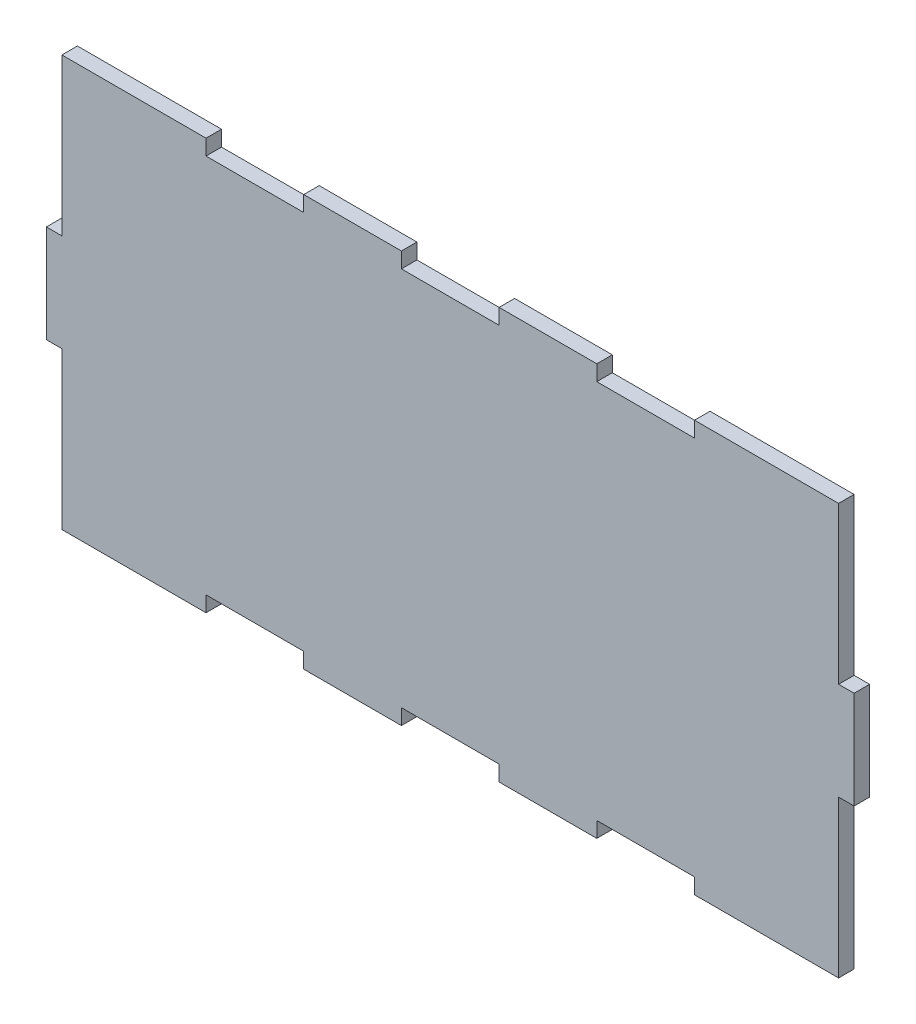
SolidWorks part; units mm, degrees
ref_plane "Plan de face" through (0, 0, 0) normal (0, 0, 1) x (1, 0, 0)
ref_plane "Plan de dessus" through (0, 0, 0) normal (0, 1, 0) x (1, 0, 0)
ref_plane "Plan de droite" through (0, 0, 0) normal (1, 0, 0) x (0, 0, -1)
sketch "Esquisse1" plane through (0, 0, 0) normal (0, 0, 1) x (1, 0, 0)
  line L0 (-82.675, 42.073) -> (-82.675, -42.073)
  line L1 (-82.675, 42.073) -> (82.675, 42.073)
  line L3 (-82.675, -42.073) -> (82.675, -42.073)
  line L4 (82.675, 42.073) -> (82.675, -42.073)
  point P4 (0, -42.073)
  point P6 (82.675, 0)
  point P7 (-82.675, 0)
  dimension "D1" = 84.146
  dimension "D2" = 165.35
extrude "Boss.-Extru.1" add sketch "Esquisse1" along normal blind 3.175
sketch "Esquisse4" plane through (0, 0, 3.175) normal (0, 0, 1) x (1, 0, 0)
  line L0 (-82.675, 42.073) -> (-82.675, -42.073) construction
  line L1 (-82.675, 10) -> (-76.325, 10)
  line L2 (-82.675, 10) -> (-82.675, -10)
  line L3 (-82.675, -10) -> (-76.325, -10)
  line L4 (-76.325, 10) -> (-76.325, -10)
  point P6 (-76.325, 0)
  dimension "D1" = 20
  dimension "D2" = 6.35
sketch "Esquisse2" plane through (0, 0, 3.175) normal (0, 0, 1) x (1, 0, 0)
  line L0 (-82.675, 42.073) -> (-82.675, -42.073) construction
  line L1 (-82.675, -42.073) -> (-79.5, -42.073)
  line L2 (-82.675, -42.073) -> (-82.675, -10)
  line L3 (-82.675, -10) -> (-79.5, -10)
  line L4 (-79.5, -42.073) -> (-79.5, -10)
  line L9 (-82.675, 10) -> (-79.5, 10)
  line L10 (-82.675, 10) -> (-82.675, 42.073)
  line L11 (-82.675, 42.073) -> (-79.5, 42.073)
  line L12 (-79.5, 10) -> (-79.5, 42.073)
  line L13 (-82.675, -42.073) -> (82.675, -42.073) construction
  line L14 (-82.675, 10) -> (-76.325, 10) construction
  line L15 (82.675, 42.073) -> (-82.675, 42.073) construction
  line L16 (-82.675, -10) -> (-76.325, -10) construction
  dimension "D1" = 3.175
extrude "Enlèv. mat.-Extru.1" cut sketch "Esquisse2" against normal through all
mirror "Symétrie1" about plane through (0, 0, 0) normal (1, 0, 0) of "Enlèv. mat.-Extru.1"
sketch "Esquisse3" plane through (0, 0, 3.175) normal (0, 0, 1) x (1, 0, 0)
  line L0 (-79.5, -42.073) -> (79.5, -42.073) construction
  line L1 (-10, -42.073) -> (10, -42.073)
  line L2 (-10, -42.073) -> (-10, -38.898)
  line L3 (-10, -38.898) -> (10, -38.898)
  line L4 (10, -42.073) -> (10, -38.898)
  line L6 (30, -42.073) -> (50, -42.073)
  line L7 (30, -42.073) -> (30, -38.898)
  line L8 (30, -38.898) -> (50, -38.898)
  line L9 (50, -42.073) -> (50, -38.898)
  line L10 (-30, -42.073) -> (-50, -42.073)
  line L11 (-30, -42.073) -> (-30, -38.898)
  line L12 (-30, -38.898) -> (-50, -38.898)
  line L13 (-50, -42.073) -> (-50, -38.898)
  point P14 (0, -38.898)
  point P16 (30, -40.4855)
  point P17 (10, -40.4855)
  dimension "D1" = 20
  dimension "D2" = 20
  dimension "D3" = 20
  dimension "D4" = 3.175
extrude "Enlèv. mat.-Extru.2" cut sketch "Esquisse3" against normal through all
mirror "Symétrie2" about plane through (0, 0, 0) normal (0, 1, 0) of "Enlèv. mat.-Extru.2"
